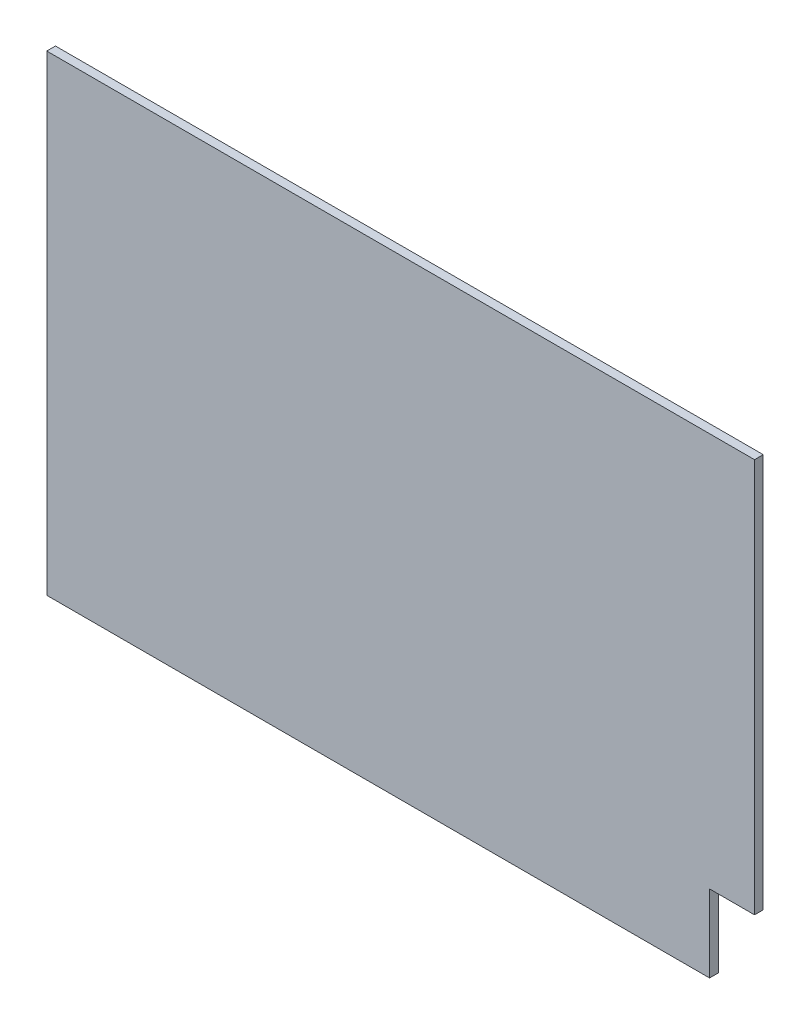
SolidWorks part; units mm, degrees
ref_plane "Front Plane" through (0, 0, 0) normal (0, 0, 1) x (1, 0, 0)
ref_plane "Top Plane" through (0, 0, 0) normal (0, 1, 0) x (1, 0, 0)
ref_plane "Right Plane" through (0, 0, 0) normal (1, 0, 0) x (0, 0, -1)
sketch "Sketch1" plane through (0, 0, 0) normal (0, 0, 1) x (1, 0, 0)
  line L1 (0, 0) -> (2285, 0)
  line L2 (0, 0) -> (0, 1625)
  line L3 (0, 1625) -> (2440, 1625)
  line L4 (2440, 266) -> (2440, 1625)
  line L7 (2440, 266) -> (2285, 266)
  line L8 (2285, 0) -> (2285, 266)
  dimension "D1" = 2440
  dimension "D2" = 1625
  dimension "D3" = 155
  dimension "D4" = 266
extrude "Boss-Extrude1" add sketch "Sketch1" along normal blind 30
